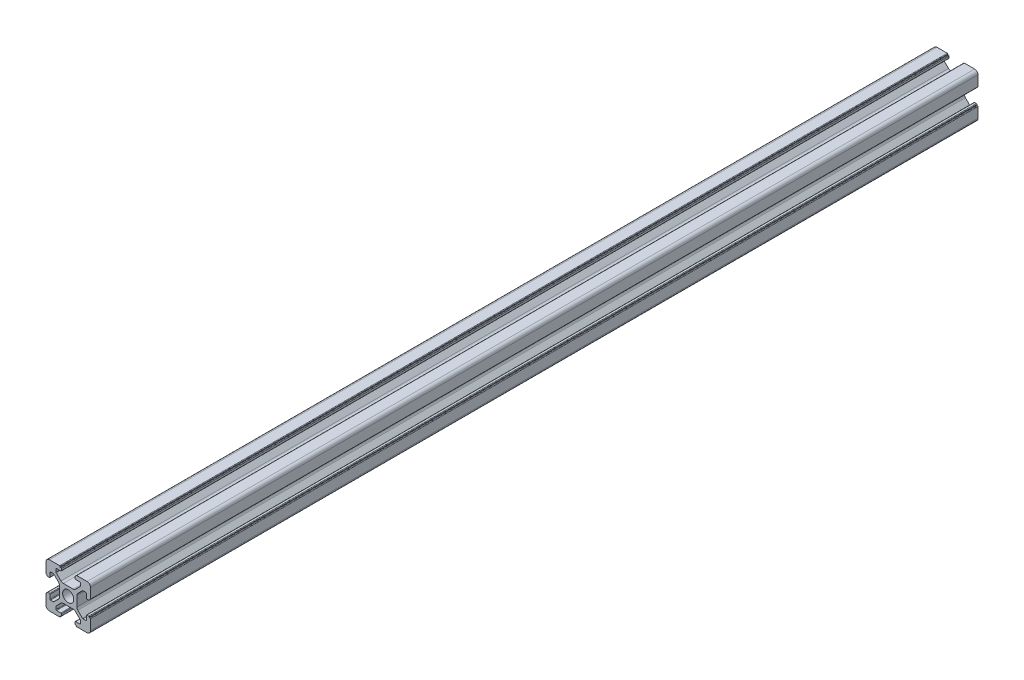
SolidWorks part; units mm, degrees
ref_plane "前视基准面" through (0, 0, 0) normal (0, 0, 1) x (1, 0, 0)
ref_plane "上视基准面" through (0, 0, 0) normal (0, 1, 0) x (1, 0, 0)
ref_plane "右视基准面" through (0, 0, 0) normal (1, 0, 0) x (0, 0, -1)
sketch "草图1" plane through (0, 0, 0) normal (0, 0, 1) x (1, 0, 0)
  line L0 (0, 0) -> (0, 5.5) construction
  line L1 (-8.5023, -10.0023) -> (-3.85, -10.0023)
  line L2 (-10.0023, -8.5023) -> (-10.0023, -3.85)
  line L3 (-8.5023, 10.0023) -> (-3.85, 10.0023)
  line L4 (10.0023, -8.5023) -> (10.0023, -3.85)
  line L5 (-10.0023, -10.0023) -> (10.0023, 10.0023) construction
  line L6 (-10.0023, 10.0023) -> (10.0023, -10.0023) construction
  line L7 (-2.218, -3.9) -> (2.218, -3.9)
  line L8 (-3.9, -2.218) -> (-3.9, 2.218)
  line L9 (-2.218, 3.9) -> (2.218, 3.9)
  line L10 (3.9, -2.218) -> (3.9, 2.218)
  line L11 (-3.9, -3.9) -> (3.9, 3.9) construction
  line L12 (-3.9, 3.9) -> (3.9, -3.9) construction
  line L13 (-5.25, -8.2) -> (-3.35, -8.2)
  line L14 (-8.2, -5.25) -> (-8.2, -3.35)
  line L15 (-5.25, 8.2) -> (-3.35, 8.2)
  line L16 (8.2, -5.25) -> (8.2, -3.35)
  line L17 (-8.2, -8.2) -> (8.2, 8.2) construction
  line L18 (-8.2, 8.2) -> (8.2, -8.2) construction
  line L19 (-7.95, 5.5) -> (-6.6642, 5.5)
  line L20 (0, 0) -> (5.5, 0) construction
  line L23 (-5.5, 7.95) -> (-5.5, 6.6642)
  line L26 (0, 0) -> (-0.5303, 0.5303)
  line L27 (3.2787, 4.3393) -> (5.4268, 6.4874)
  line L28 (0, 0) -> (0.5303, -0.5303)
  line L29 (5.5, 6.6642) -> (5.5, 7.95)
  line L30 (4.3393, 3.2787) -> (6.4874, 5.4268)
  line L31 (6.6642, 5.5) -> (7.95, 5.5)
  line L32 (4.3393, -3.2787) -> (6.4874, -5.4268)
  line L33 (3.2787, -4.3393) -> (5.4268, -6.4874)
  line L34 (-3.2787, -4.3393) -> (-5.4268, -6.4874)
  line L35 (-4.3393, -3.2787) -> (-6.4874, -5.4268)
  line L36 (-4.3393, 3.2787) -> (-6.4874, 5.4268)
  line L37 (-3.2787, 4.3393) -> (-5.4268, 6.4874)
  line L38 (3.1, -8.45) -> (3.1, -9.2523)
  line L39 (8.45, 3.1) -> (9.2523, 3.1)
  line L40 (-5.5, -6.6642) -> (-5.5, -7.95)
  line L41 (-6.6642, -5.5) -> (-7.95, -5.5)
  line L42 (5.5, -6.6642) -> (5.5, -7.95)
  line L43 (6.6642, -5.5) -> (7.95, -5.5)
  line L44 (9.2523, -3.1) -> (8.45, -3.1)
  line L46 (10.0023, 3.85) -> (10.0023, 8.5023)
  line L47 (8.2, 3.35) -> (8.2, 5.25)
  line L48 (-3.1, -9.2523) -> (-3.1, -8.45)
  line L49 (-8.45, -3.1) -> (-9.2523, -3.1)
  line L50 (-9.2523, 3.1) -> (-8.45, 3.1)
  line L51 (-3.1, 8.45) -> (-3.1, 9.2523)
  line L52 (3.1, 9.2523) -> (3.1, 8.45)
  line L53 (3.85, 10.0023) -> (8.5023, 10.0023)
  line L54 (3.35, 8.2) -> (5.25, 8.2)
  line L55 (-10.0023, 3.85) -> (-10.0023, 8.5023)
  line L56 (-8.2, 3.35) -> (-8.2, 5.25)
  line L57 (3.35, -8.2) -> (5.25, -8.2)
  line L58 (3.85, -10.0023) -> (8.5023, -10.0023)
  line L59 (9.7523, -3.6) -> (9.5023, -3.6)
  line L61 (9.7523, 3.6) -> (9.5023, 3.6)
  line L62 (9.5023, -3.6) -> (9.5023, -3.35)
  line L63 (3.6, -9.7523) -> (3.6, -9.5023)
  line L64 (3.35, -9.5023) -> (3.6, -9.5023)
  line L65 (9.5023, 3.35) -> (9.5023, 3.6)
  line L66 (-3.6, -9.5023) -> (-3.35, -9.5023)
  line L67 (-3.6, -9.7523) -> (-3.6, -9.5023)
  line L68 (-9.7523, -3.6) -> (-9.5023, -3.6)
  line L69 (-9.5023, -3.35) -> (-9.5023, -3.6)
  line L70 (-9.5023, 3.6) -> (-9.5023, 3.35)
  line L71 (-9.7523, 3.6) -> (-9.5023, 3.6)
  line L72 (-3.6, 9.7523) -> (-3.6, 9.5023)
  line L73 (-3.35, 9.5023) -> (-3.6, 9.5023)
  line L74 (3.6, 9.5023) -> (3.35, 9.5023)
  line L75 (3.6, 9.7523) -> (3.6, 9.5023)
  circle A0 centre (0, 0) radius 2.5
  arc A1 (10.0023, 8.5023) -> (8.5023, 10.0023) centre (8.5023, 8.5023) ccw
  arc A2 (8.5023, -10.0023) -> (10.0023, -8.5023) centre (8.5023, -8.5023) ccw
  arc A3 (-10.0023, -8.5023) -> (-8.5023, -10.0023) centre (-8.5023, -8.5023) ccw
  arc A4 (-10.0023, 8.5023) -> (-8.5023, 10.0023) centre (-8.5023, 8.5023) cw
  arc A5 (-9.5023, -3.35) -> (-9.2523, -3.1) centre (-9.2523, -3.35) cw
  arc A6 (-9.7523, -3.6) -> (-10.0023, -3.85) centre (-9.7523, -3.85) ccw
  arc A7 (-8.45, -3.1) -> (-8.2, -3.35) centre (-8.45, -3.35) cw
  arc A8 (-7.95, -5.5) -> (-8.2, -5.25) centre (-7.95, -5.25) cw
  arc A9 (-6.4874, -5.4268) -> (-6.6642, -5.5) centre (-6.6642, -5.25) cw
  arc A10 (-5.4268, -6.4874) -> (-5.5, -6.6642) centre (-5.25, -6.6642) ccw
  arc A11 (-5.5, -7.95) -> (-5.25, -8.2) centre (-5.25, -7.95) ccw
  arc A12 (-3.6, -9.7523) -> (-3.85, -10.0023) centre (-3.85, -9.7523) cw
  arc A13 (-3.35, -9.5023) -> (-3.1, -9.2523) centre (-3.35, -9.2523) ccw
  arc A14 (-3.1, -8.45) -> (-3.35, -8.2) centre (-3.35, -8.45) ccw
  arc A15 (3.1, -8.45) -> (3.35, -8.2) centre (3.35, -8.45) cw
  arc A16 (5.5, -7.95) -> (5.25, -8.2) centre (5.25, -7.95) cw
  arc A17 (5.4268, -6.4874) -> (5.5, -6.6642) centre (5.25, -6.6642) cw
  arc A18 (6.4874, -5.4268) -> (6.6642, -5.5) centre (6.6642, -5.25) ccw
  arc A19 (7.95, -5.5) -> (8.2, -5.25) centre (7.95, -5.25) ccw
  arc A20 (8.45, -3.1) -> (8.2, -3.35) centre (8.45, -3.35) ccw
  arc A21 (9.5023, -3.35) -> (9.2523, -3.1) centre (9.2523, -3.35) ccw
  arc A22 (9.7523, -3.6) -> (10.0023, -3.85) centre (9.7523, -3.85) cw
  arc A23 (3.35, -9.5023) -> (3.1, -9.2523) centre (3.35, -9.2523) cw
  arc A24 (3.6, -9.7523) -> (3.85, -10.0023) centre (3.85, -9.7523) ccw
  arc A25 (7.95, 5.5) -> (8.2, 5.25) centre (7.95, 5.25) cw
  arc A26 (8.2, 3.35) -> (8.45, 3.1) centre (8.45, 3.35) ccw
  arc A27 (9.5023, 3.35) -> (9.2523, 3.1) centre (9.2523, 3.35) cw
  arc A28 (9.7523, 3.6) -> (10.0023, 3.85) centre (9.7523, 3.85) ccw
  arc A29 (6.6642, 5.5) -> (6.4874, 5.4268) centre (6.6642, 5.25) ccw
  arc A30 (5.4268, 6.4874) -> (5.5, 6.6642) centre (5.25, 6.6642) ccw
  arc A31 (5.5, 7.95) -> (5.25, 8.2) centre (5.25, 7.95) ccw
  arc A32 (3.1, 8.45) -> (3.35, 8.2) centre (3.35, 8.45) ccw
  arc A33 (3.6, 9.7523) -> (3.85, 10.0023) centre (3.85, 9.7523) cw
  arc A34 (3.35, 9.5023) -> (3.1, 9.2523) centre (3.35, 9.2523) ccw
  arc A35 (-9.7523, 3.6) -> (-10.0023, 3.85) centre (-9.7523, 3.85) cw
  arc A36 (-9.5023, 3.35) -> (-9.2523, 3.1) centre (-9.2523, 3.35) ccw
  arc A37 (-8.45, 3.1) -> (-8.2, 3.35) centre (-8.45, 3.35) ccw
  arc A38 (-8.2, 5.25) -> (-7.95, 5.5) centre (-7.95, 5.25) cw
  arc A39 (-6.4874, 5.4268) -> (-6.6642, 5.5) centre (-6.6642, 5.25) ccw
  arc A40 (-5.4268, 6.4874) -> (-5.5, 6.6642) centre (-5.25, 6.6642) cw
  arc A41 (-5.5, 7.95) -> (-5.25, 8.2) centre (-5.25, 7.95) cw
  arc A42 (-3.1, 8.45) -> (-3.35, 8.2) centre (-3.35, 8.45) cw
  arc A43 (-3.1, 9.2523) -> (-3.35, 9.5023) centre (-3.35, 9.2523) ccw
  arc A44 (-3.6, 9.7523) -> (-3.85, 10.0023) centre (-3.85, 9.7523) ccw
  arc A45 (-4.3393, 3.2787) -> (-3.9, 2.218) centre (-5.4, 2.218) cw
  arc A46 (-3.2787, 4.3393) -> (-2.218, 3.9) centre (-2.218, 5.4) ccw
  arc A47 (3.2787, 4.3393) -> (2.218, 3.9) centre (2.218, 5.4) cw
  arc A48 (4.3393, 3.2787) -> (3.9, 2.218) centre (5.4, 2.218) ccw
  arc A49 (4.3393, -3.2787) -> (3.9, -2.218) centre (5.4, -2.218) cw
  arc A50 (3.2787, -4.3393) -> (2.218, -3.9) centre (2.218, -5.4) ccw
  arc A51 (-4.3393, -3.2787) -> (-3.9, -2.218) centre (-5.4, -2.218) ccw
  arc A52 (-2.218, -3.9) -> (-3.2787, -4.3393) centre (-2.218, -5.4) ccw
  point P0 (0, 0)
  point P7 (10.0023, 0)
  point P62 (0, 0)
  point P76 (0, 0)
  point P92 (-8.2, -5.5)
  point P99 (0, 0)
  point P106 (-5.5, -8.2)
  point P117 (5.5, -8.2)
  point P124 (8.2, -5.5)
  point P137 (8.2, 5.5)
  point P140 (8.2, 3.1)
  point P147 (6.5607, 5.5)
  point P152 (5.5, 8.2)
  point P167 (-8.2, 5.5)
  point P174 (-5.5, 8.2)
  dimension "D1" = 1.5
  dimension "D5" = 0.25
  dimension "D6" = 1.5
  dimension "D2" = 4
  dimension "D3" = 4
  dimension "D4" = 4
extrude "凸台-拉伸1" add sketch "草图1" along normal blind 400 contours A52 L7 A50 L33 A17 L42 A16 L57 A15 L38 A23 L64 L63 A24 L58 A2 L4 A22 L59 L62 A21 L44 A20 L16 A19 L43 A18 L32 A49 L10 A48 L30 A29 L31 A25 L47 A26 L39 A27 L65 L61 A28 L46 A1 L53 A33 L75 L74 A34 L52 A32
